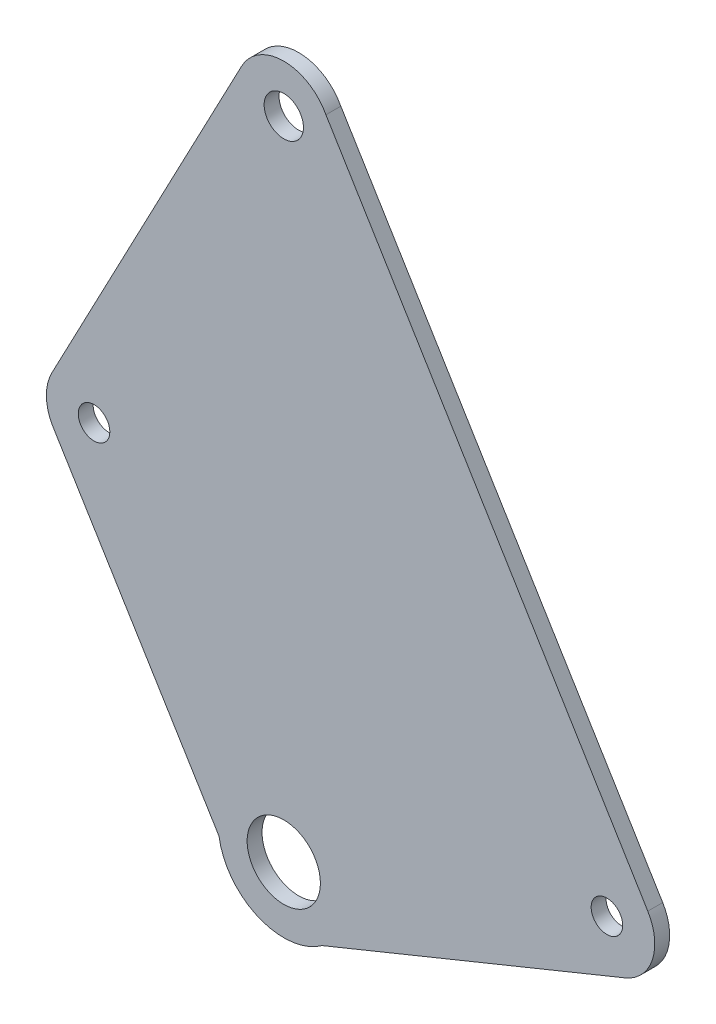
SolidWorks part; units mm, degrees
material "Custom Plastic"
ref_plane "X-Y Datum" through (0, 0, 0) normal (0, 0, 1) x (1, 0, 0)
ref_plane "X-Z Datum" through (0, 0, 0) normal (0, 1, 0) x (1, 0, 0)
ref_plane "Y-Z Datum" through (0, 0, 0) normal (1, 0, 0) x (0, 0, -1)
sketch "Rocker Ref Sketch" plane through (0, 0, 0) normal (0, 0, 1) x (1, 0, 0)
  line L0 (0, 0) -> (0, 137.7747) construction
  line L1 (0, 137.7747) -> (40.4627, 60.9059) construction
  line L2 (40.4627, 60.9059) -> (0, 0) construction
  line L3 (-13.97, 0) -> (-10.16, 137.7747)
  line L4 (8.9905, 142.5072) -> (49.4532, 65.6383)
  line L5 (49.4532, 56.1734) -> (8.1778, -11.3263)
  circle A0 centre (0, 0) radius 7.8105
  circle A1 centre (40.4627, 60.9059) radius 3.3655
  circle A2 centre (0, 137.7747) radius 4.191
  arc A3 (-10.16, 137.7747) -> (8.9905, 142.5072) centre (0, 137.7747) cw
  arc A4 (49.4532, 65.6383) -> (49.4532, 56.1734) centre (40.4627, 60.9059) cw
  arc A5 (8.1778, -11.3263) -> (-13.97, 0) centre (0, 0) cw
  arc A6 (-10.16, 137.7747) -> (-13.97, 0) centre (-120.7988, 71.8942) cw
  circle A7 centre (0, 0) radius 11.5718
  point P16 (50.6227, 60.9059)
  dimension "D4" = 15.621
  dimension "D5" = 6.731
  dimension "D6" = 8.382
  dimension "D7" = 13.97
  dimension "D8" = 10.16
  dimension "D9" = 10.16
  dimension "D1" = 137.7747
  dimension "D2" = 86.868
  dimension "D3" = 73.1215
  dimension "D11" = 125.83
sketch "Sketch4" plane through (0, 0, 0) normal (0, 0, 1) x (1, 0, 0)
  line L0 (8.9905, 142.5072) -> (49.4532, 65.6383) construction
  line L1 (49.4532, 65.6383) -> (8.9905, 142.5072)
  line L2 (-10.16, 137.7747) -> (-13.97, 0)
  line L3 (8.1778, -11.3263) -> (49.4532, 56.1734)
  line L4 (0, 0) -> (68.9116, 24.453)
  line L5 (8.1778, -11.3263) -> (72.764, 15.0028)
  line L6 (40.4627, 60.9059) -> (-12.2857, 60.9059) construction
  line L7 (0, 137.7747) -> (0, 0) construction
  line L8 (0, 0) -> (0, 137.7747) construction
  line L9 (10.16, 137.7747) -> (13.97, 0)
  line L10 (-49.4532, 65.6383) -> (-8.9905, 142.5072)
  line L11 (-8.1778, -11.3263) -> (-49.4532, 56.1734)
  line L12 (8.9905, 142.5072) -> (77.6286, 29.7597)
  circle A1 centre (40.4627, 60.9059) radius 3.3655
  arc A2 (49.4532, 56.1734) -> (49.4532, 65.6383) centre (40.4627, 60.9059) ccw
  circle A3 centre (0, 137.7747) radius 4.191
  circle A5 centre (0, 0) radius 7.8105
  arc A6 (8.9905, 142.5072) -> (-10.16, 137.7747) centre (0, 137.7747) ccw
  arc A7 (8.9905, 142.5072) -> (-10.16, 137.7747) centre (0, 137.7747) ccw construction
  arc A8 (-13.97, 0) -> (8.1778, -11.3263) centre (0, 0) ccw
  arc A9 (-13.97, 0) -> (8.1778, -11.3263) centre (0, 0) ccw construction
  circle A10 centre (-40.4627, 60.9059) radius 3.3655
  arc A11 (13.97, 0) -> (-8.1778, -11.3263) centre (0, 0) cw
  arc A12 (-8.9905, 142.5072) -> (10.16, 137.7747) centre (0, 137.7747) cw
  arc A13 (-49.4532, 56.1734) -> (-49.4532, 65.6383) centre (-40.4627, 60.9059) cw
  circle A14 centre (68.9116, 24.453) radius 3.3655
  arc A16 (77.6286, 29.7597) -> (72.764, 15.0028) centre (68.9116, 24.453) cw
  dimension "D1" = 6.731
  dimension "D2" = 8.382
  dimension "D3" = 15.621
  dimension "D8" = 6.731
  dimension "D9" = 10.2053
  dimension "D4" = 79.1193
  dimension "D5" = 137.7747
  dimension "D6" = 70.463
  dimension "D7" = 73.1215
extrude "Boss-Extrude4" add sketch "Sketch4" along normal blind 3.175
